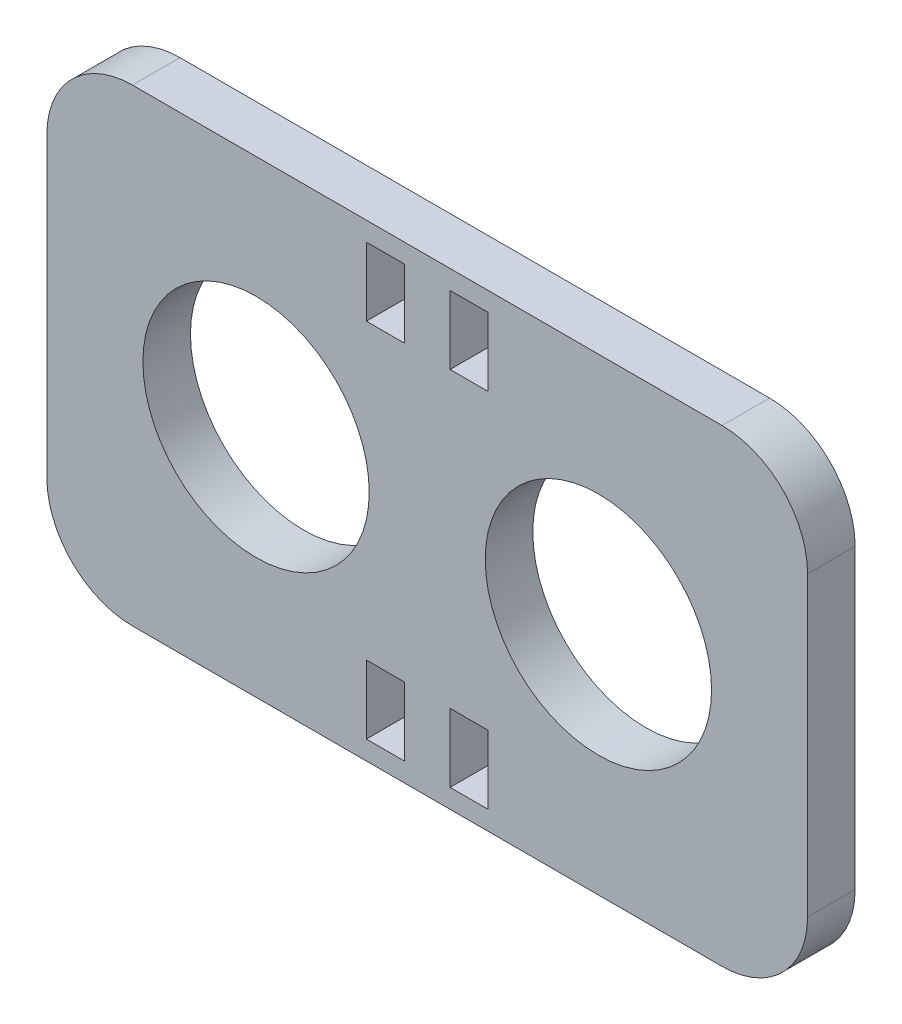
SolidWorks part; units mm, degrees
ref_plane "Front Plane" through (0, 0, 0) normal (0, 0, 1) x (1, 0, 0)
ref_plane "Top Plane" through (0, 0, 0) normal (0, 1, 0) x (1, 0, 0)
ref_plane "Right Plane" through (0, 0, 0) normal (1, 0, 0) x (0, 0, -1)
sketch "Sketch1" plane through (0, 0, 0) normal (0, 0, 1) x (1, 0, 0)
  line L0 (12.065, -6.2325) -> (22.86, -12.465)
  line L7 (-10.795, -6.2325) -> (0, -12.465)
  line L8 (0, -12.465) -> (10.795, -6.2325)
  line L9 (10.795, -6.2325) -> (10.795, 6.2325)
  line L10 (10.795, 6.2325) -> (0, 12.465)
  line L11 (0, 12.465) -> (-10.795, 6.2325)
  line L12 (-10.795, 6.2325) -> (-10.795, -6.2325)
  line L13 (22.86, -12.465) -> (33.655, -6.2325)
  line L14 (33.655, -6.2325) -> (33.655, 6.2325)
  line L15 (33.655, 6.2325) -> (22.86, 12.465)
  line L16 (22.86, 12.465) -> (12.065, 6.2325)
  line L17 (12.065, 6.2325) -> (12.065, -6.2325)
  line L24 (0, 0) -> (0, 12.465) construction
  line L49 (-8.255, 12.465) -> (31.115, 12.465)
  line L50 (-10.795, 9.925) -> (-10.795, -9.925)
  line L51 (-8.255, -12.465) -> (31.115, -12.465)
  line L52 (33.655, 9.925) -> (33.655, -9.925)
  line L53 (-8.255, 15.64) -> (31.115, 15.64)
  line L54 (36.83, 9.925) -> (36.83, -9.925)
  line L55 (-8.255, -15.64) -> (31.115, -15.64)
  line L56 (-13.97, 9.925) -> (-13.97, -9.925)
  line L57 (10.795, 6.2325) -> (12.065, 6.2325) construction
  line L59 (11.43, 6.2325) -> (11.43, 15.64) construction
  line L60 (11.43, 14.37) -> (12.954, 14.37) construction
  line L61 (7.366, 14.37) -> (7.366, 9.798)
  line L62 (12.954, 14.37) -> (15.494, 14.37)
  line L63 (12.954, 14.37) -> (12.954, 9.798)
  line L64 (12.954, 9.798) -> (15.494, 9.798)
  line L65 (15.494, 14.37) -> (15.494, 9.798)
  line L66 (9.906, 9.798) -> (7.366, 9.798)
  line L67 (9.906, 14.37) -> (9.906, 9.798)
  line L68 (9.906, 14.37) -> (7.366, 14.37)
  line L69 (0, 0) -> (-13.97, 0) construction
  line L102 (15.494, -14.37) -> (15.494, -9.798)
  line L103 (12.954, -9.798) -> (15.494, -9.798)
  line L104 (12.954, -14.37) -> (12.954, -9.798)
  line L105 (12.954, -14.37) -> (15.494, -14.37)
  line L106 (9.906, -14.37) -> (7.366, -14.37)
  line L107 (9.906, -14.37) -> (9.906, -9.798)
  line L108 (9.906, -9.798) -> (7.366, -9.798)
  line L109 (7.366, -14.37) -> (7.366, -9.798)
  line L111 (9.906, 14.37) -> (12.954, 14.37)
  line L112 (9.906, 14.37) -> (9.906, 9.798)
  line L113 (9.906, 9.798) -> (12.954, 9.798)
  line L114 (12.954, 14.37) -> (12.954, 9.798)
  line L131 (9.906, -9.798) -> (12.954, -9.798)
  line L132 (9.906, -9.798) -> (9.906, -14.37)
  line L133 (9.906, -14.37) -> (12.954, -14.37)
  line L134 (12.954, -9.798) -> (12.954, -14.37)
  circle A0 centre (0, 0) radius 7.5565
  circle A1 centre (0, 0) radius 10.795 construction
  circle A2 centre (22.86, 0) radius 7.5565
  circle A3 centre (22.86, 0) radius 10.795 construction
  arc A7 (-8.255, 12.465) -> (-10.795, 9.925) centre (-8.255, 9.925) ccw
  arc A13 (33.655, 9.925) -> (31.115, 12.465) centre (31.115, 9.925) ccw
  arc A14 (-10.795, -9.925) -> (-8.255, -12.465) centre (-8.255, -9.925) ccw
  arc A15 (33.655, -9.925) -> (31.115, -12.465) centre (31.115, -9.925) cw
  arc A16 (36.83, 9.925) -> (31.115, 15.64) centre (31.115, 9.925) ccw
  arc A17 (36.83, -9.925) -> (31.115, -15.64) centre (31.115, -9.925) cw
  arc A18 (-13.97, -9.925) -> (-8.255, -15.64) centre (-8.255, -9.925) ccw
  arc A19 (-8.255, 15.64) -> (-13.97, 9.925) centre (-8.255, 9.925) ccw
  point P0 (0, 0)
  point P8 (22.86, 0)
  point P57 (-45.72, 0)
  dimension "D1" = 15.113
  dimension "D8" = 3.175
  dimension "D5" = 2.54
  dimension "D6" = 2.54
  dimension "D7" = 2.54
  dimension "D2" = 21.59
  dimension "D4" = 22.86
  dimension "D9" = 24.93
  dimension "D10" = 1.524
  dimension "D11" = 2.54
  dimension "D12" = 1.27
  dimension "D13" = 4.572
  dimension "D3" = 2
extrude "Boss-Extrude1" add sketch "Sketch1" along normal blind 3.175
ref_plane "Plane1" through (11.43, 0, 0) normal (1, 0, 0) x (0, 0, -1)
